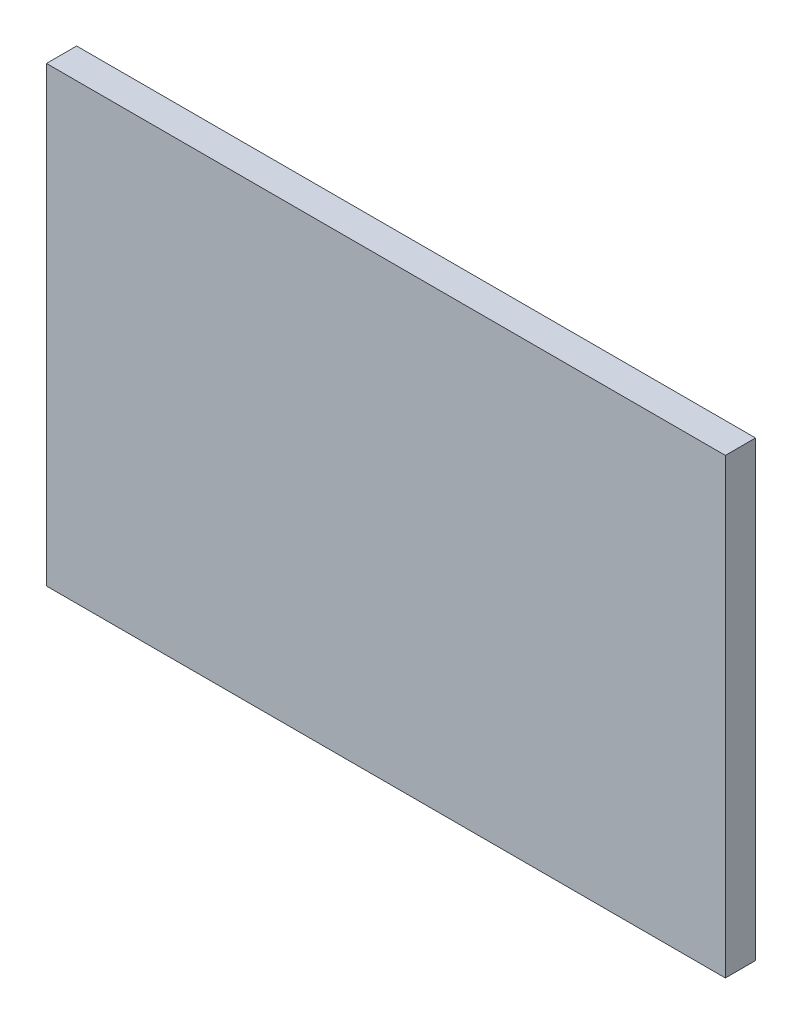
SolidWorks part; units mm, degrees
ref_plane "Front" through (0, 0, 0) normal (0, 0, 1) x (1, 0, 0)
ref_plane "Top" through (0, 0, 0) normal (0, 1, 0) x (1, 0, 0)
ref_plane "Right" through (0, 0, 0) normal (1, 0, 0) x (0, 0, -1)
sketch "Sketch1" plane through (0, 0, 0) normal (0, 0, 1) x (1, 0, 0)
  line L1 (-22.5, 15) -> (22.5, 15)
  line L2 (-22.5, 15) -> (-22.5, -15)
  line L3 (-22.5, -15) -> (22.5, -15)
  line L4 (22.5, 15) -> (22.5, -15)
  line L5 (-22.5, 15) -> (22.5, -15) construction
  line L6 (-22.5, -15) -> (22.5, 15) construction
  point P0 (0, 0)
  dimension "D1" = 30
  dimension "D2" = 45
extrude "Boss-Extrude1" add sketch "Sketch1" along normal blind 2
